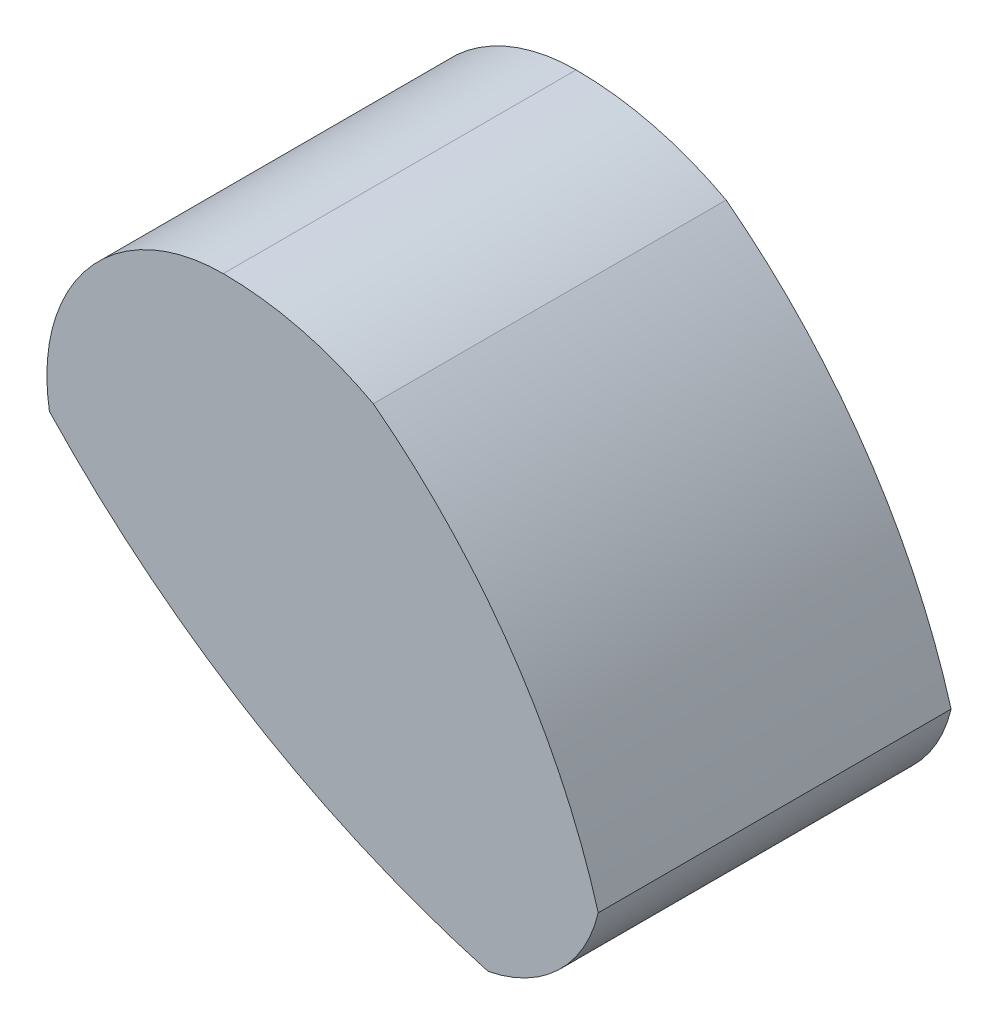
SolidWorks part; units mm, degrees
ref_plane "Front Plane" through (0, 0, 0) normal (0, 0, 1) x (1, 0, 0)
ref_plane "Top Plane" through (0, 0, 0) normal (0, 1, 0) x (1, 0, 0)
ref_plane "Right Plane" through (0, 0, 0) normal (1, 0, 0) x (0, 0, -1)
sketch "Sketch1" plane through (0, 0, 0) normal (0, 0, 1) x (1, 0, 0)
  line L1 (10.6276, -5.3741) -> (7.5046, -5.3741)
  arc A0 (-4.9277, -0.8474) -> (7.5046, -8.3741) centre (14.7558, 17.6339) ccw
  arc A2 (7.5046, -8.3741) -> (10.6276, -5.3741) centre (6.7362, -4.4486) ccw
  arc A4 (6.5977, -5.158) -> (-4.9277, -0.8474) centre (-26.404, -75.8325) ccw
  arc A5 (10.6276, -5.3741) -> (4.2517, 3.9324) centre (-6.6618, -10.3818) ccw
  arc A6 (0, 5) -> (-4.9277, -0.8474) centre (0, 0) ccw
  arc A7 (4.2517, 3.9324) -> (0, 5) centre (0, -4) ccw
  spline S1 degree 3 poles (6.5977, -5.158) (6.7404, -5.2246) (6.8871, -5.2773) (7.1896, -5.352) (7.3467, -5.3741) (7.5046, -5.3741) knots 0 0 0 0 0.5 0.5 1 1 1 1
  dimension "D1" = 9
  dimension "D2" = 5
  dimension "D3" = 18
  dimension "D4" = 78
  dimension "D15" = 4
  dimension "D16" = 27
  dimension "D5" = 4.2517
  dimension "D6" = 1.0676
  dimension "D7" = 9.3066
  dimension "D8" = 6.3759
  dimension "D9" = 3.123
  dimension "D10" = 0.2161
  dimension "D11" = 0.9069
  dimension "D12" = 11.5254
  dimension "D13" = 4.3106
  dimension "D14" = 5.8474
  dimension "D17" = 3
sketch "Sketch3" plane through (0, 0, 0) normal (0, 0, 1) x (1, 0, 0)
  arc A0 (7.5046, -8.3741) -> (10.6276, -5.3741) centre (6.7362, -4.4486) ccw construction
  arc A1 (10.6276, -5.3741) -> (4.2517, 3.9324) centre (-6.6618, -10.3818) ccw construction
  arc A2 (4.2517, 3.9324) -> (0, 5) centre (0, -4) ccw construction
  arc A3 (0, 5) -> (-4.9277, -0.8474) centre (0, 0) ccw construction
  arc A6 (10.6276, -5.3741) -> (4.2517, 3.9324) centre (-6.6618, -10.3818) ccw
  arc A7 (4.2517, 3.9324) -> (0, 5) centre (0, -4) ccw
  arc A8 (0, 5) -> (-4.9277, -0.8474) centre (0, 0) ccw
  arc A10 (-4.9277, -0.8474) -> (7.5046, -8.3741) centre (14.7558, 17.6339) ccw construction
  arc A11 (-4.9277, -0.8474) -> (7.5046, -8.3741) centre (14.7558, 17.6339) ccw
  arc A12 (7.5046, -8.3741) -> (10.6276, -5.3741) centre (6.7362, -4.4486) ccw
extrude "Boss-Extrude3" add sketch "Sketch3" along normal blind 10
sketch "Sketch5" plane through (0, 0, 0) normal (0, 0, 1) x (1, 0, 0)
  line L2 (6.5977, -5.158) -> (6.5977, 1.7914)
  line L4 (6.5977, -5.158) -> (6.5977, -8.1041)
  arc A0 (-4.9277, -0.8474) -> (7.5046, -8.3741) centre (14.7558, 17.6339) ccw construction
  arc A1 (0, 5) -> (-4.9277, -0.8474) centre (0, 0) ccw construction
  arc A2 (4.2517, 3.9324) -> (0, 5) centre (0, -4) ccw construction
  arc A3 (10.6276, -5.3741) -> (4.2517, 3.9324) centre (-6.6618, -10.3818) ccw construction
  arc A4 (6.5977, -5.158) -> (-4.9277, -0.8474) centre (-26.404, -75.8325) ccw construction
  arc A5 (-4.9277, -0.8474) -> (6.5977, -8.1041) centre (14.7558, 17.6339) ccw
  arc A6 (0, 5) -> (-4.9277, -0.8474) centre (0, 0) ccw
  arc A7 (4.2517, 3.9324) -> (0, 5) centre (0, -4) ccw
  arc A8 (6.5977, 1.7914) -> (4.2517, 3.9324) centre (-6.6618, -10.3818) ccw
  arc A9 (6.5977, -5.158) -> (-4.9277, -0.8474) centre (-26.404, -75.8325) ccw
sketch "Sketch4" plane through (0, 0, 0) normal (0, 0, 1) x (1, 0, 0)
  line L0 (10.6276, -5.3741) -> (7.5046, -5.3741) construction
  line L1 (10.6276, -5.3741) -> (7.5046, -5.3741)
  arc A0 (6.5977, -5.158) -> (-4.9277, -0.8474) centre (-26.404, -75.8325) ccw construction
  arc A1 (10.6276, -5.3741) -> (4.2517, 3.9324) centre (-6.6618, -10.3818) ccw construction
  arc A2 (4.2517, 3.9324) -> (0, 5) centre (0, -4) ccw construction
  arc A3 (0, 5) -> (-4.9277, -0.8474) centre (0, 0) ccw construction
  arc A4 (6.5977, -5.158) -> (-4.9277, -0.8474) centre (-26.404, -75.8325) ccw
  arc A5 (10.6276, -5.3741) -> (4.2517, 3.9324) centre (-6.6618, -10.3818) ccw
  arc A6 (4.2517, 3.9324) -> (0, 5) centre (0, -4) ccw
  arc A7 (0, 5) -> (-4.9277, -0.8474) centre (0, 0) ccw
  spline S0 degree 3 poles (-606.7237, -1908.4177) (37.8602, 238.379) (-11.6557, -0.699) (16.168, -7.5688) (46.9323, 45.4663) (-1045.0956, 1694.4171) knots -61.313464 -61.313464 -61.313464 -61.313464 0.5 0.5 30.687913 30.687913 30.687913 30.687913 only from (6.5977, -5.158) to (7.5046, -5.3741) construction
  spline S1 degree 3 poles (6.5977, -5.158) (6.7404, -5.2246) (6.8871, -5.2773) (7.1896, -5.352) (7.3467, -5.3741) (7.5046, -5.3741) knots 0 0 0 0 0.5 0.5 1 1 1 1
hole_wizard "M3 Clearance Hole1" positions "Sketch8" profile "Sketch9" hole size "M3" standard "ISO"
sketch "Sketch8" plane through (0, 0, 0) normal (0, 0, -1) x (-1, 0, 0)
  point P0 (0, 2)
  dimension "D1" = 2
sketch "Sketch9" plane through (0, 2, 0) normal (1, 0, 0) x (0, 1, 0)
  line L0 (0, 0) -> (0, 6.5815)
  line L1 (0, 6.5815) -> (1.8, 5.5)
  line L2 (1.8, 5.5) -> (1.8, 0)
  line L5 (1.8, 0) -> (0, 0)
  line L10 (0, 6.5815) -> (-1.8, 5.5) construction
  line L11 (0, -6.35) -> (0, 107.95) construction
  dimension "Hole Dia." = 3.6
  dimension "Hole Depth" = 5.5
  dimension "Drill Angle" = 118
